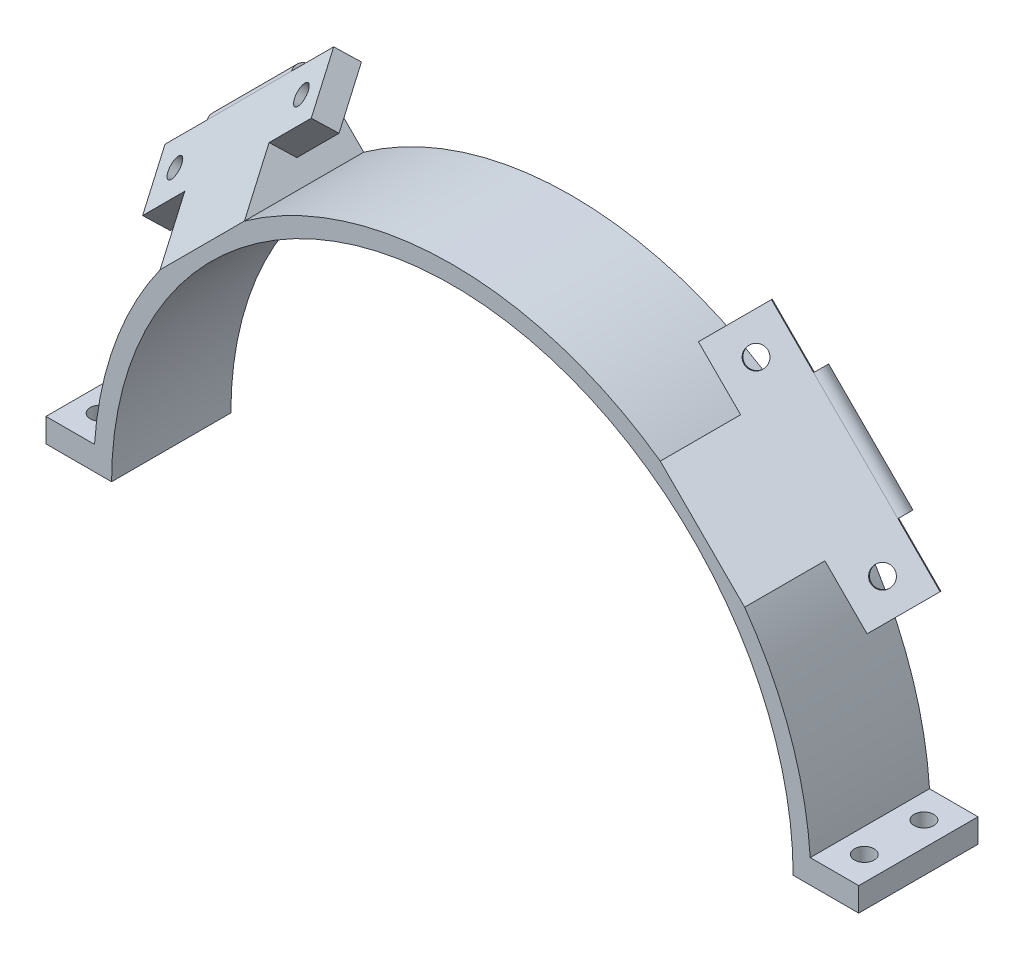
SolidWorks part; units mm, degrees
ref_plane "正面" through (0, 0, 0) normal (0, 0, 1) x (1, 0, 0)
ref_plane "平面" through (0, 0, 0) normal (0, 1, 0) x (1, 0, 0)
ref_plane "右側面" through (0, 0, 0) normal (1, 0, 0) x (0, 0, -1)
sketch "ｽｹｯﾁ1" plane through (0, 0, 0) normal (0, 0, 1) x (1, 0, 0)
  line L0 (-57.15, 0) -> (57.15, 0) construction
  line L1 (-57.15, 0) -> (-60.15, 0)
  line L2 (57.15, 0) -> (60.15, 0)
  arc A0 (-57.15, 0) -> (57.15, 0) centre (0, 0) cw
  arc A1 (-60.15, 0) -> (60.15, 0) centre (0, 0) cw
  dimension "D1" = 114.3
  dimension "D2" = 3
extrude "ﾎﾞｽ - 押し出し1" add sketch "ｽｹｯﾁ1" along normal blind 20
sketch "ｽｹｯﾁ3" plane through (0, 0, 20) normal (0, 0, 1) x (1, 0, 0)
  line L0 (0, 0) -> (-42.5325, 42.5325) construction
  line L1 (-60.15, 0) -> (-57.15, 0) construction
  line L2 (-41.9406, 41.9406) -> (-34.8695, 49.0116)
  line L3 (-34.8695, 49.0116) -> (-45.4761, 59.6182)
  line L4 (-45.4761, 59.6182) -> (-59.6182, 45.4761)
  line L5 (-59.6182, 45.4761) -> (-49.0116, 34.8695)
  line L6 (-49.0116, 34.8695) -> (-41.9406, 41.9406)
  line L7 (0, 0) -> (0, 60.15) construction
  line L8 (59.6182, 45.4761) -> (49.0116, 34.8695)
  line L9 (45.4761, 59.6182) -> (59.6182, 45.4761)
  line L10 (34.8695, 49.0116) -> (45.4761, 59.6182)
  line L11 (41.9406, 41.9406) -> (34.8695, 49.0116)
  line L12 (49.0116, 34.8695) -> (41.9406, 41.9406)
  arc A0 (60.15, 0) -> (-60.15, 0) centre (0, 0) ccw construction
  dimension "D1" = 45
  dimension "D2" = 20
  dimension "D3" = 15
extrude "ﾎﾞｽ - 押し出し2" add sketch "ｽｹｯﾁ3" against normal up to surface (20 mm away) up to face at (0, 29.325, 0)
sketch "ｽｹｯﾁ4" plane through (-7.0711, -7.0711, 0) normal (-0.7071, -0.7071, 0) x (0, 0, 1)
  line L0 (0, 74.3129) -> (20, 59.3129)
  line L1 (20, 59.3129) -> (20, 74.3129)
  line L2 (20, 74.3129) -> (0, 74.3129)
extrude "ｶｯﾄ - 押し出し1" cut sketch "ｽｹｯﾁ4" against normal up to next
sketch "ｽｹｯﾁ5" plane through (7.0711, -7.0711, 0) normal (0.7071, -0.7071, 0) x (0, 0, -1)
  line L0 (0, 74.3129) -> (-20, 59.3129)
  line L1 (-20, 59.3129) -> (-20, 74.3129)
  line L2 (-20, 74.3129) -> (0, 74.3129)
extrude "ｶｯﾄ - 押し出し2" cut sketch "ｽｹｯﾁ5" against normal up to next
sketch "ｽｹｯﾁ6" plane through (-33.6302, 33.6302, 35.6702) normal (-0.5657, 0.5657, 0.6) x (0.8246, 0.3881, 0.4116)
  line L0 (-22.9402, 38.2337) -> (-10.0778, 16.7964) construction
  line L1 (-14.3653, 43.3786) -> (-31.5151, 33.0887) construction
  line L2 (-1.5029, 21.9413) -> (-18.6527, 11.6514) construction
  line L3 (-7.9341, 32.66) -> (-25.0839, 22.3701) construction
  line L4 (-14.3653, 43.3786) -> (-1.5029, 21.9413) construction
  line L5 (-31.5151, 33.0887) -> (-18.6527, 11.6514) construction
  line L6 (-29.4572, 29.6588) -> (-38.0321, 24.5138)
  line L7 (-26.8847, 25.3713) -> (-18.6527, 11.6514) construction
  line L8 (-38.0321, 24.5138) -> (-32.8871, 15.9389)
  line L9 (-32.8871, 15.9389) -> (-24.3122, 21.0838)
  line L10 (-24.3122, 21.0838) -> (-29.4572, 29.6588)
  line L11 (1.4126, 36.5187) -> (-7.1623, 31.3737)
  line L12 (-3.7324, 45.0936) -> (1.4126, 36.5187)
  line L13 (-12.3073, 39.9487) -> (-3.7324, 45.0936)
  line L14 (-7.1623, 31.3737) -> (-12.3073, 39.9487)
  dimension "D1" = 10
  dimension "D2" = 10
  dimension "D3" = 11
extrude "ﾎﾞｽ - 押し出し3" add sketch "ｽｹｯﾁ6" against normal blind 4
sketch "ｽｹｯﾁ7" plane through (33.6302, 33.6302, 35.6702) normal (0.5657, 0.5657, 0.6) x (0.8246, -0.3881, -0.4116)
  line L0 (22.9402, 38.2337) -> (10.0778, 16.7964) construction
  line L1 (31.5151, 33.0887) -> (14.3653, 43.3786) construction
  line L2 (1.5029, 21.9413) -> (18.6527, 11.6514) construction
  line L3 (12.3073, 39.9487) -> (7.1623, 31.3737)
  line L4 (1.5029, 21.9413) -> (14.3653, 43.3786) construction
  line L5 (9.7348, 35.6612) -> (1.5029, 21.9413) construction
  line L6 (7.1623, 31.3737) -> (-1.4126, 36.5187)
  line L7 (-1.4126, 36.5187) -> (3.7324, 45.0936)
  line L8 (3.7324, 45.0936) -> (12.3073, 39.9487)
  line L9 (32.8871, 15.9389) -> (38.0321, 24.5138)
  line L10 (24.3122, 21.0838) -> (32.8871, 15.9389)
  line L11 (29.4572, 29.6588) -> (24.3122, 21.0838)
  line L12 (38.0321, 24.5138) -> (29.4572, 29.6588)
  dimension "D1" = 10
  dimension "D2" = 10
  dimension "D3" = 11
extrude "ﾎﾞｽ - 押し出し4" add sketch "ｽｹｯﾁ7" against normal blind 4
sketch "ｽｹｯﾁ8" plane through (33.6302, 33.6302, 35.6702) normal (0.5657, 0.5657, 0.6) x (0.8246, -0.3881, -0.4116)
  line L0 (1.1599, 40.8062) -> (35.4596, 20.2263) construction
  line L1 (3.7324, 45.0936) -> (-1.4126, 36.5187) construction
  line L2 (32.8871, 15.9389) -> (38.0321, 24.5138) construction
  circle A0 centre (5.4474, 38.2337) radius 1.65
  circle A1 centre (31.1721, 22.7988) radius 1.65
  dimension "D1" = 3.3
  dimension "D3" = 5
  dimension "D2" = 5
extrude "ｶｯﾄ - 押し出し3" cut sketch "ｽｹｯﾁ8" against normal up to next
sketch "ｽｹｯﾁ9" plane through (-33.6302, 33.6302, 35.6702) normal (-0.5657, 0.5657, 0.6) x (0.8246, 0.3881, 0.4116)
  line L0 (-1.1599, 40.8062) -> (-35.4596, 20.2263) construction
  line L1 (1.4126, 36.5187) -> (-3.7324, 45.0936) construction
  line L2 (-38.0321, 24.5138) -> (-32.8871, 15.9389) construction
  circle A0 centre (-5.4474, 38.2337) radius 1.65
  circle A1 centre (-31.1721, 22.7988) radius 1.65
  dimension "D1" = 3.3
  dimension "D3" = 5
  dimension "D2" = 5
fillet "ﾌｨﾚｯﾄ1" radius 2 2 edges at (52.5472, 52.5472, 0) (-52.5472, 52.5472, 0)
extrude "ｶｯﾄ - 押し出し4" cut sketch "ｽｹｯﾁ9" against normal up to next
sketch "ｽｹｯﾁ10" plane through (0, 0, 0) normal (0, -1, 0) x (1, 0, 0)
  line L0 (0, 0) -> (0, 20) construction
  line L1 (-57.15, 0) -> (57.15, 0) construction
  line L2 (57.15, 20) -> (-57.15, 20) construction
  line L3 (-58.15, 20) -> (-68.15, 20)
  line L4 (-68.15, 20) -> (-68.15, 0)
  line L5 (-68.15, 0) -> (-58.15, 0)
  line L6 (-58.15, 20) -> (-58.15, 0)
  line L7 (58.15, 20) -> (68.15, 20)
  line L8 (68.15, 20) -> (68.15, 0)
  line L9 (68.15, 0) -> (58.15, 0)
  line L10 (58.15, 20) -> (58.15, 0)
  line L11 (-60.15, 20) -> (-57.15, 20) construction
  line L12 (-60.15, 0) -> (-57.15, 0) construction
  line L13 (-60.15, 20) -> (-60.15, 0) construction
  dimension "D1" = 10
  dimension "D2" = 2
extrude "ﾎﾞｽ - 押し出し5" add sketch "ｽｹｯﾁ10" against normal blind 4
sketch "ｽｹｯﾁ11" plane through (0, 4, 0) normal (0, 1, 0) x (1, 0, 0)
  line L0 (64.0834, 0) -> (64.0834, -20) construction
  line L1 (60.0169, 0) -> (68.15, 0) construction
  line L2 (68.15, -20) -> (60.0169, -20) construction
  line L3 (0, 0) -> (0, -20) construction
  line L4 (-34.8695, -20) -> (34.8695, -20) construction
  circle A0 centre (64.0834, -5) radius 1.65
  circle A1 centre (64.0834, -15) radius 1.65
  circle A2 centre (-64.0834, -15) radius 1.65
  circle A3 centre (-64.0834, -5) radius 1.65
  dimension "D1" = 3.3
  dimension "D2" = 5
  dimension "D3" = 5
extrude "ｶｯﾄ - 押し出し5" cut sketch "ｽｹｯﾁ11" against normal up to next
